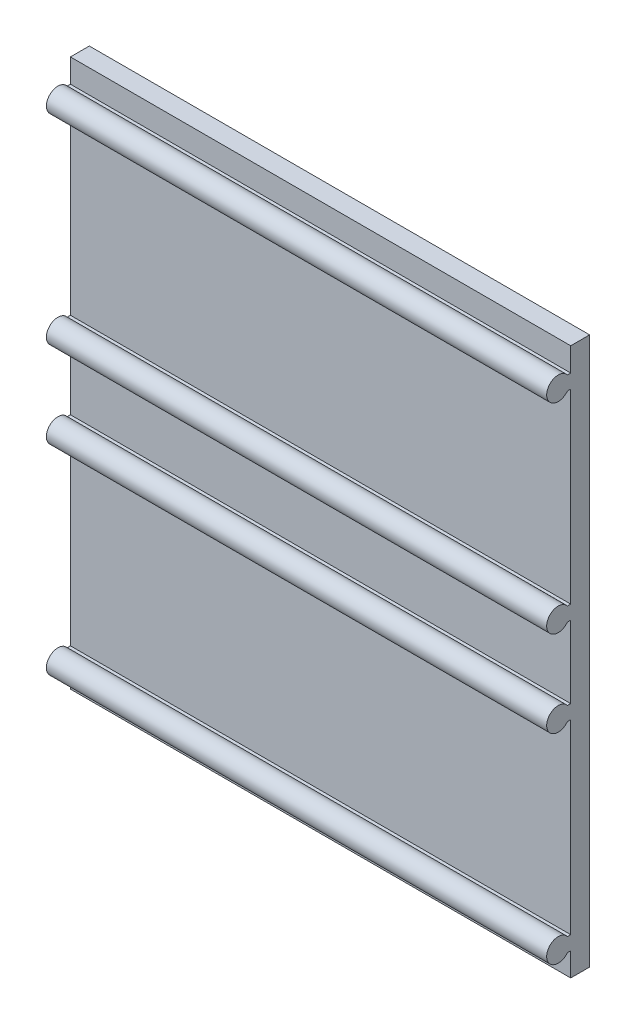
SolidWorks part; units mm, degrees
ref_plane "Спереди" through (0, 0, 0) normal (0, 0, 1) x (1, 0, 0)
ref_plane "Сверху" through (0, 0, 0) normal (0, 1, 0) x (1, 0, 0)
ref_plane "Справа" through (0, 0, 0) normal (1, 0, 0) x (0, 0, -1)
ref_plane "Плоскость4" through (90, 0, 0) normal (1, 0, 0) x (0, 0, -1)
sketch "Эскиз1" plane through (90, 0, 0) normal (1, 0, 0) x (0, 0, -1)
  line L0 (6.75, 225.9062) -> (6.75, 320.75)
  line L1 (6.75, 320.75) -> (-38.0938, 320.75)
  line L2 (-38.0938, 318.25) -> (-37.5, 318.25)
  line L3 (-37.5, 318.25) -> (-37.5, 284.75)
  line L4 (-37.5, 284.75) -> (-38.0938, 284.75)
  line L5 (-38.0938, 282.25) -> (-37.5, 282.25)
  line L6 (-37.5, 282.25) -> (-37.5, 269.25)
  line L7 (-37.5, 269.25) -> (-38.0938, 269.25)
  line L8 (-38.0938, 266.75) -> (-37.5, 266.75)
  line L9 (-37.5, 266.75) -> (-37.5, 233.25)
  line L10 (-37.5, 233.25) -> (-38.0938, 233.25)
  line L11 (-38.0938, 230.75) -> (-37.5, 230.75)
  line L12 (-37.5, 230.75) -> (-37.5, 226.5)
  line L13 (-37.5, 226.5) -> (-33.25, 226.5)
  line L14 (-33.25, 226.5) -> (-33.25, 225.9062)
  line L15 (-30.75, 225.9062) -> (-30.75, 226.5)
  line L16 (-30.75, 226.5) -> (-22.25, 226.5)
  line L17 (-22.25, 226.5) -> (-22.25, 225.9062)
  line L18 (-19.75, 225.9062) -> (-19.75, 226.5)
  line L19 (-19.75, 226.5) -> (-6.75, 226.5)
  line L20 (-6.75, 226.5) -> (-6.75, 225.9062)
  line L21 (-4.25, 225.9062) -> (-4.25, 226.5)
  line L22 (-4.25, 226.5) -> (4.25, 226.5)
  line L23 (4.25, 226.5) -> (4.25, 225.9062)
  arc A0 (-38.0938, 320.75) -> (-38.0938, 318.25) centre (-39.75, 319.5) ccw
  arc A1 (-38.0938, 284.75) -> (-38.0938, 282.25) centre (-39.75, 283.5) ccw
  arc A2 (-38.0938, 269.25) -> (-38.0938, 266.75) centre (-39.75, 268) ccw
  arc A3 (-38.0938, 233.25) -> (-38.0938, 230.75) centre (-39.75, 232) ccw
  arc A4 (-33.25, 225.9062) -> (-30.75, 225.9062) centre (-32, 224.25) ccw
  arc A5 (-22.25, 225.9062) -> (-19.75, 225.9062) centre (-21, 224.25) ccw
  arc A6 (-6.75, 225.9062) -> (-4.25, 225.9062) centre (-5.5, 224.25) ccw
  arc A7 (4.25, 225.9062) -> (6.75, 225.9062) centre (5.5, 224.25) ccw
extrude "Бобышка-Вытянуть1" add sketch "Эскиз1" against normal blind 90
sketch "Эскиз2" plane through (0, 320.75, 0) normal (0, 1, 0) x (-1, 0, 0)
  line L0 (-90, -6.75) -> (-90, 37.5)
  line L1 (-90, 37.5) -> (0, 37.5)
  line L2 (0, 37.5) -> (0, -6.75)
  line L3 (0, -6.75) -> (-90, -6.75)
extrude "Бобышка-Вытянуть2" add sketch "Эскиз2" along normal blind 8.2
sketch "Эскиз3" plane through (0, 0, -6.75) normal (0, 0, -1) x (-1, 0, 0)
  line L0 (-90, 226.5) -> (-90, 328.95)
  line L1 (-90, 328.95) -> (0, 328.95)
  line L2 (0, 328.95) -> (0, 226.5)
  line L3 (0, 226.5) -> (-90, 226.5)
extrude "Бобышка-Вытянуть3" add sketch "Эскиз3" along normal blind 8.2
sketch "Эскиз4" plane through (0, 0, 0) normal (-1, 0, 0) x (0, 0, 1)
  line L0 (24.25, 328.95) -> (24.25, 325)
  line L1 (24.25, 325) -> (28.75, 325)
  line L2 (28.75, 325) -> (28.75, 328.95)
  line L3 (28.75, 328.95) -> (24.25, 328.95)
extrude "Вырез-Вытянуть1" cut sketch "Эскиз4" against normal through all
sketch "Эскиз5" plane through (0, 0, 0) normal (-1, 0, 0) x (0, 0, 1)
  line L0 (37.5, 328.95) -> (35.25, 328.95)
  line L1 (35.25, 328.95) -> (35.25, 325)
  line L2 (35.25, 325) -> (37.5, 325)
  line L3 (37.5, 325) -> (37.5, 328.95)
extrude "Вырез-Вытянуть2" cut sketch "Эскиз5" against normal through all
sketch "Эскиз6" plane through (0, 0, 0) normal (-1, 0, 0) x (0, 0, 1)
  line L0 (-14.95, 226.5) -> (-11, 226.5)
  line L1 (-11, 226.5) -> (-11, 228.75)
  line L2 (-11, 228.75) -> (-14.95, 228.75)
  line L3 (-14.95, 228.75) -> (-14.95, 226.5)
extrude "Вырез-Вытянуть3" cut sketch "Эскиз6" against normal through all
sketch "Эскиз7" plane through (0, 0, 0) normal (-1, 0, 0) x (0, 0, 1)
  line L0 (-14.95, 235.25) -> (-11, 235.25)
  line L1 (-11, 235.25) -> (-11, 264.75)
  line L2 (-11, 264.75) -> (-14.95, 264.75)
  line L3 (-14.95, 264.75) -> (-14.95, 235.25)
extrude "Вырез-Вытянуть4" cut sketch "Эскиз7" against normal through all
sketch "Эскиз8" plane through (0, 0, 0) normal (-1, 0, 0) x (0, 0, 1)
  line L0 (-14.95, 271.25) -> (-11, 271.25)
  line L1 (-11, 271.25) -> (-11, 280.25)
  line L2 (-11, 280.25) -> (-14.95, 280.25)
  line L3 (-14.95, 280.25) -> (-14.95, 271.25)
extrude "Вырез-Вытянуть5" cut sketch "Эскиз8" against normal through all
sketch "Эскиз9" plane through (0, 0, 0) normal (-1, 0, 0) x (0, 0, 1)
  line L0 (-14.95, 286.75) -> (-11, 286.75)
  line L1 (-11, 286.75) -> (-11, 316.25)
  line L2 (-11, 316.25) -> (-14.95, 316.25)
  line L3 (-14.95, 316.25) -> (-14.95, 286.75)
extrude "Вырез-Вытянуть6" cut sketch "Эскиз9" against normal through all
sketch "Эскиз10" plane through (0, 0, 0) normal (-1, 0, 0) x (0, 0, 1)
  line L0 (-14.95, 328.95) -> (-14.95, 322.75)
  line L1 (-14.95, 322.75) -> (-11, 322.75)
  line L2 (-11, 322.75) -> (-11, 328.95)
  line L3 (-11, 328.95) -> (-14.95, 328.95)
extrude "Вырез-Вытянуть7" cut sketch "Эскиз10" against normal through all
sketch "Эскиз11" plane through (0, 0, 0) normal (-1, 0, 0) x (0, 0, 1)
  line L0 (-11, 328.95) -> (-11, 325)
  line L1 (-11, 325) -> (-8.75, 325)
  line L2 (-8.75, 325) -> (-8.75, 328.95)
  line L3 (-8.75, 328.95) -> (-11, 328.95)
extrude "Вырез-Вытянуть8" cut sketch "Эскиз11" against normal through all
sketch "Эскиз12" plane through (0, 0, 0) normal (-1, 0, 0) x (0, 0, 1)
  line L0 (-2.25, 328.95) -> (-2.25, 325)
  line L1 (-2.25, 325) -> (2.25, 325)
  line L2 (2.25, 325) -> (2.25, 328.95)
  line L3 (2.25, 328.95) -> (-2.25, 328.95)
extrude "Вырез-Вытянуть9" cut sketch "Эскиз12" against normal through all
sketch "Эскиз13" plane through (0, 0, 0) normal (-1, 0, 0) x (0, 0, 1)
  line L0 (8.75, 328.95) -> (8.75, 325)
  line L1 (8.75, 325) -> (17.75, 325)
  line L2 (17.75, 325) -> (17.75, 328.95)
  line L3 (17.75, 328.95) -> (8.75, 328.95)
extrude "Вырез-Вытянуть10" cut sketch "Эскиз13" against normal through all
sketch "Эскиз14" plane through (90, 0, 0) normal (1, 0, 0) x (0, 0, -1)
  line L0 (9.6, 323.6) -> (-36.1, 323.6)
  line L1 (-36.1, 323.6) -> (-36.1, 227.9)
  line L2 (-36.1, 227.9) -> (9.6, 227.9)
  line L3 (9.6, 227.9) -> (9.6, 323.6)
extrude "Вырез-Вытянуть11" cut sketch "Эскиз14" against normal blind 86
hole_wizard "Диаметр отверстия Ø2.5 (2.5)1" positions "Эскиз16" profile "Эскиз15" hole size "Ø2.5" standard "Ansi Metric"
sketch "Эскиз16" plane through (90, 0, 0) normal (1, 0, 0) x (0, 0, -1)
  point P0 (-39.75, 232)
  point P1 (-21, 224.25)
  point P2 (-39.75, 283.5)
  point P3 (-5.5, 224.25)
  point P4 (5.5, 224.25)
  point P5 (-39.75, 319.5)
  point P6 (-39.75, 268)
  point P7 (-32, 224.25)
sketch "Эскиз15" plane through (90, 232, 39.75) normal (0, 1, 0) x (0, 0, -1)
  line L0 (0, 0) -> (0, 90)
  line L1 (0, 90) -> (1.25, 90)
  line L2 (1.25, 90) -> (1.25, 0)
  line L5 (1.25, 0) -> (0, 0)
  line L11 (0, -6.35) -> (0, 107.95) construction
  dimension "Диаметр сквозного отверстия" = 2.5
  dimension "Глубина сквозного отверстия" = 90
hole_wizard "Диаметр отверстия Ø4.5 (4.5)1" positions "Эскиз18" profile "Эскиз17" hole size "Ø4.5" standard "Ansi Metric"
sketch "Эскиз18" plane through (0, 0, 0) normal (-1, 0, 0) x (0, 0, 1)
  point P0 (21, 327.25)
  point P1 (32, 327.25)
  point P2 (-13.25, 232)
  point P3 (-13.25, 268)
  point P4 (-13.25, 283.5)
  point P5 (-13.25, 319.5)
  point P6 (-5.5, 327.25)
  point P7 (5.5, 327.25)
sketch "Эскиз17" plane through (0, 327.25, 21) normal (0, 1, 0) x (0, 0, 1)
  line L0 (0, 0) -> (0, 90)
  line L1 (0, 90) -> (2.25, 90)
  line L2 (2.25, 90) -> (2.25, 0)
  line L5 (2.25, 0) -> (0, 0)
  line L11 (0, -6.35) -> (0, 107.95) construction
  dimension "Диаметр сквозного отверстия" = 4.5
  dimension "Глубина сквозного отверстия" = 90
hole_wizard "Диаметр отверстия Ø8.3 (8.3)1" positions "Эскиз20" profile "Эскиз19" hole size "Ø8.3" standard "Ansi Metric"
sketch "Эскиз20" plane through (0, 0, 0) normal (-1, 0, 0) x (0, 0, 1)
  point P0 (13.25, 275.75)
sketch "Эскиз19" plane through (0, 275.75, 13.25) normal (0, 1, 0) x (0, 0, 1)
  line L0 (0, 0) -> (0, 3.2)
  line L1 (0, 3.2) -> (4.15, 3.2)
  line L2 (4.15, 3.2) -> (4.15, 0)
  line L5 (4.15, 0) -> (0, 0)
  line L10 (0, 3.2) -> (-4.15, 3.2) construction
  line L11 (0, -6.35) -> (0, 107.95) construction
  dimension "Диаметр отверстия" = 8.3
  dimension "Глубина отверстия" = 3.2
  dimension "Угол заточки сверла" = 180
sketch "Эскиз21" plane through (0, 0, 0) normal (-1, 0, 0) x (0, 0, 1)
  circle A0 centre (13.25, 275.75) radius 4.15
extrude "Вырез-Вытянуть12" cut sketch "Эскиз21" against normal blind 10
sketch "Эскиз22" plane through (90, 0, 0) normal (1, 0, 0) x (0, 0, -1)
  circle A0 centre (-39.75, 319.5) radius 1.6316
  circle A1 centre (-39.75, 283.5) radius 1.5194
  circle A2 centre (-39.75, 268) radius 1.4876
  circle A3 centre (-39.75, 232) radius 1.5817
  circle A4 centre (-32, 224.25) radius 1.4878
  circle A5 centre (-21, 224.25) radius 1.426
  circle A6 centre (-5.5, 224.25) radius 1.6281
  circle A7 centre (5.5, 224.25) radius 1.5237
extrude "Бобышка-Вытянуть4" add sketch "Эскиз22" against normal blind 90
fillet "Скругление1" radius 2 1 edges at (4, 275.75, -9.6)
fillet "Скругление2" radius 2 1 edges at (4, 275.75, 36.1)
fillet "Скругление3" radius 2 3 edges at (4, 323.6, 13.25) (4.5858, 323.6, -9.0142) (4.5858, 323.6, 35.5142)
fillet "Скругление4" radius 2 3 edges at (4.5858, 227.9, -9.0142) (4, 227.9, 13.25) (4.5858, 227.9, 35.5142)
fillet "Скругление5" radius 2 1 edges at (45, 325, 35.25)
fillet "Скругление6" radius 2 1 edges at (45, 325, 28.75)
fillet "Скругление7" radius 2 1 edges at (45, 325, 24.25)
fillet "Скругление8" radius 2 1 edges at (45, 325, 17.75)
fillet "Скругление9" radius 2 1 edges at (45, 325, 8.75)
fillet "Скругление10" radius 2 1 edges at (45, 325, 2.25)
fillet "Скругление11" radius 2 1 edges at (45, 325, -2.25)
fillet "Скругление12" radius 2 1 edges at (45, 325, -8.75)
fillet "Скругление13" radius 2 1 edges at (45, 322.75, -11)
fillet "Скругление14" radius 2 1 edges at (45, 316.25, -11)
fillet "Скругление15" radius 2 1 edges at (45, 286.75, -11)
fillet "Скругление16" radius 2 1 edges at (45, 280.25, -11)
fillet "Скругление17" radius 2 1 edges at (45, 271.25, -11)
fillet "Скругление18" radius 2 1 edges at (45, 264.75, -11)
fillet "Скругление19" radius 2 1 edges at (45, 235.25, -11)
fillet "Скругление20" radius 2 1 edges at (45, 228.75, -11)
sketch "Эскиз23" plane through (90, 0, 0) normal (1, 0, 0) x (0, 0, -1)
  line L0 (-36.1, 323.6) -> (-36.1, 227.9) construction
  line L1 (-36.1, 323.6) -> (-36.1, 227.9)
  line L2 (-36.1, 323.6) -> (-36.1, 342.5782)
  line L3 (-36.1, 342.5782) -> (21.2373, 342.5782)
  line L4 (21.2373, 342.5782) -> (21.2373, 217.7944)
  line L5 (21.2373, 217.7944) -> (-36.1, 217.7944)
  line L6 (-36.1, 217.7944) -> (-36.1, 227.9)
extrude "Вырез-Вытянуть13" cut sketch "Эскиз23" against normal blind 115
sketch "Эскиз24" plane through (90, 0, 0) normal (1, 0, 0) x (0, 0, -1)
  line L0 (-36.1, 325.3637) -> (-36.1, 226.5) construction
  line L1 (-36.1, 325.3637) -> (-36.1, 325)
  line L2 (-37.25, 325) -> (-36.1, 325)
  arc A0 (-37.25, 325) -> (-36.1, 325.3637) centre (-37.25, 327) ccw construction
  arc A1 (-37.25, 325) -> (-36.1, 325.3637) centre (-37.25, 327) ccw
extrude "Вырез-Вытянуть14" cut sketch "Эскиз24" against normal blind 115
sketch "Эскиз25" plane through (0, 0, 36.1) normal (0, 0, -1) x (-1, 0, 0)
  line L4 (0, 226.5) -> (0, 325)
  line L5 (0, 325) -> (-90, 325)
  line L6 (-90, 325) -> (-90, 226.5)
  line L7 (-90, 226.5) -> (0, 226.5)
  line L8 (0, 226.5) -> (0, 325)
  line L9 (0, 325) -> (-90, 325)
  line L10 (-90, 325) -> (-90, 226.5)
  line L11 (-90, 226.5) -> (0, 226.5)
  dimension "D1" = 0
extrude "Бобышка-Вытянуть5" add sketch "Эскиз25" along normal blind 2
